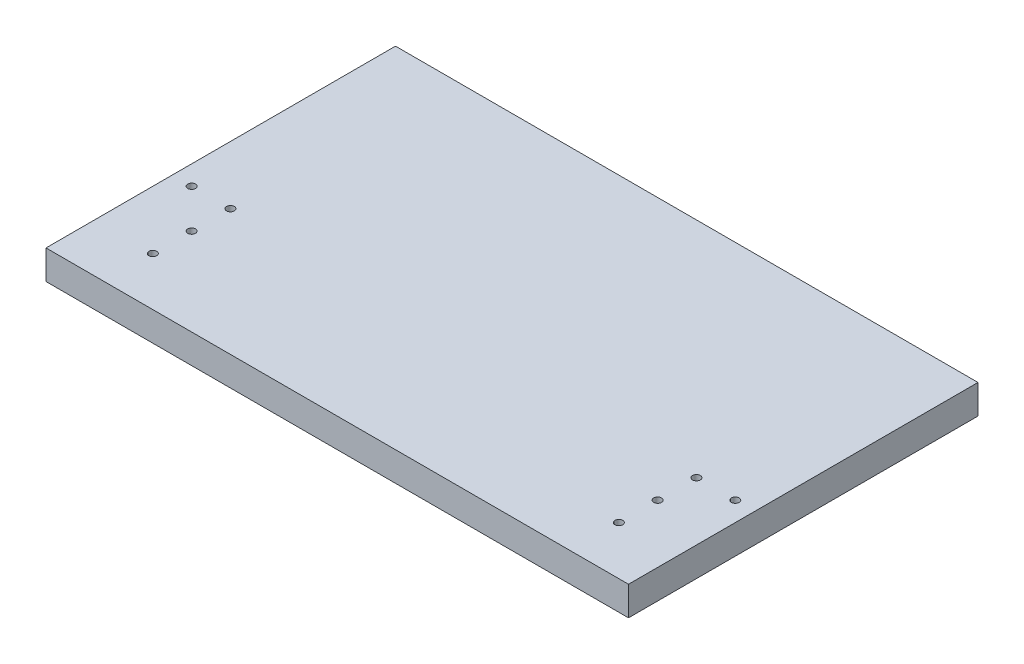
SolidWorks part; units mm, degrees
ref_plane "Alzado" through (0, 0, 0) normal (0, 0, 1) x (1, 0, 0)
ref_plane "Planta" through (0, 0, 0) normal (0, 1, 0) x (1, 0, 0)
ref_plane "Vista lateral" through (0, 0, 0) normal (1, 0, 0) x (0, 0, -1)
sketch "Croquis1" plane through (0, 0, 0) normal (0, 1, 0) x (1, 0, 0)
  line L1 (-150, -90) -> (150, -90)
  line L2 (-150, -90) -> (-150, 90)
  line L3 (-150, 90) -> (150, 90)
  line L4 (150, -90) -> (150, 90)
  line L5 (-150, -90) -> (150, 90) construction
  line L6 (-150, 90) -> (150, -90) construction
  point P0 (0, 0)
  dimension "D1" = 300
  dimension "D2" = 180
extrude "Saliente-Extruir1" add sketch "Croquis1" along normal blind 15
sketch "Croquis2" plane through (0, 15, 0) normal (0, 1, 0) x (1, 0, 0)
  line L1 (-150, -90) -> (150, -90) construction
  line L2 (-150, 90) -> (-150, -90) construction
  line L3 (150, -90) -> (150, 90) construction
  circle A0 centre (-120, -65) radius 2
  circle A1 centre (-120, -45) radius 2
  circle A2 centre (120, -65) radius 2
  circle A3 centre (120, -45) radius 2
  circle A4 centre (-140, -25) radius 2
  circle A5 centre (-120, -25) radius 2
  circle A6 centre (120, -25) radius 2
  circle A7 centre (140, -25) radius 2
  dimension "D1" = 25
  dimension "D2" = 0
  dimension "D3" = 25
  dimension "D4" = 0
  dimension "D7" = 10
  dimension "D8" = 20
  dimension "D9" = 30
  dimension "D10" = 10
  dimension "D5" = 30
  dimension "D6" = 30
  dimension "D11" = 65
  dimension "D12" = 0
  dimension "D13" = 65
  dimension "D14" = 0
  dimension "D15" = 45
  dimension "D16" = 45
extrude "Cortar-Extruir1" cut sketch "Croquis2" against normal blind 10
